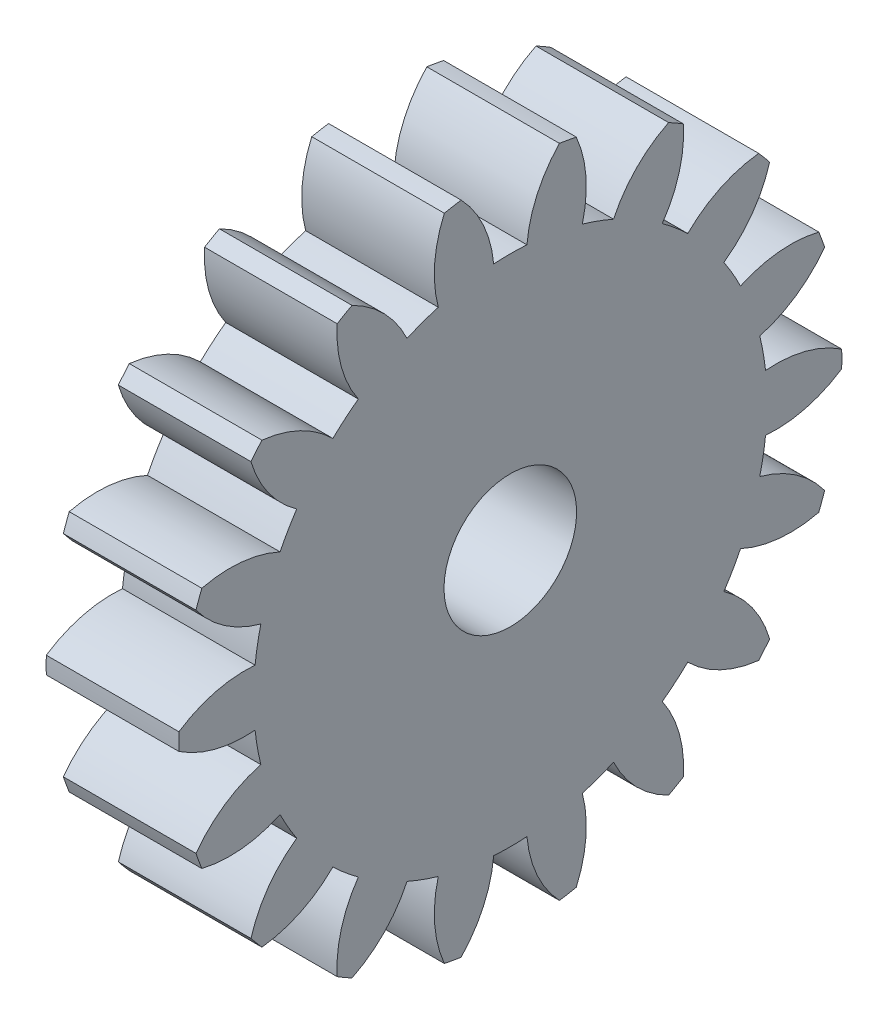
SolidWorks part; units mm, degrees
ref_plane "Plane1" through (0, 0, 0) normal (0, 0, 1) x (1, 0, 0)
ref_plane "Plane2" through (0, 0, 0) normal (0, 1, 0) x (1, 0, 0)
ref_plane "Plane3" through (0, 0, 0) normal (1, 0, 0) x (0, 0, -1)
sketch "HoldingSke" plane through (0, 0, 0) normal (0, 1, 0) x (1, 0, 0)
  line L0 (0, 0) -> (3.8042, -1.2361)
  line L1 (-15, 0) -> (100, 0) construction
  line L2 (0, 0) -> (-2.1039, 2.3779)
  line L3 (0, 0) -> (-11.863, 4.5341)
  line L4 (0, 0) -> (8.2133, 2.6687)
  line L5 (0, 0) -> (-46.8476, -17.4728)
  line L6 (0, 0) -> (-0.829, -0.5593)
  line L7 (-2.1039, 2.3779) -> (8.6586, 51.2059)
  line L8 (-76.2, 54.61) -> (-76.1, 54.61)
  line L9 (-71.009, 38.7566) -> (-53.1078, 45.2721)
  line L10 (-76.2, 71.12) -> (104.1128, 71.12)
  line L11 (0, 0) -> (-1, 0)
  line L12 (-76.2, 101.6) -> (-76.192, 101.6)
  line L13 (24.9733, 27.94) -> (52.9518, 28.4284)
  line L14 (24.9733, 27.94) -> (24.9743, 27.94)
  line L15 (24.9733, 27.94) -> (100.4006, 29.5858)
  line L16 (-63.627, -0.25) -> (-12.827, -0.25)
  circle A0 centre (0, 0) radius 0.625
  circle A1 centre (0, 0) radius 1.9365
  circle A2 centre (0, 0) radius 37.5
  circle A3 centre (0, 0) radius 0.625
  dimension "MHD" = 3.873
  dimension "Hub_dia" = 75
  dimension "Bore" = 1.25
  dimension "MBD" = 1.25
  dimension "Num_teeth" = 18
  dimension "Pitch" = 4
  dimension "Overall_len" = 50
  dimension "Show_teeth" = 18
  dimension "Thickness" = 1
  dimension "OAL" = 50.0001
  dimension "T_dim" = 0.1
  dimension "Ap" = 20
  dimension "H" = 19.05
  dimension "Pitch_radius" = 180.3128
  dimension "Width" = 1
  dimension "Backlash" = 0.008
  dimension "Addendum_fac" = 1
  dimension "Dedendum_fac" = 1.25
  dimension "Clearance_fac" = 0.25
  dimension "Dedendum_add" = 0.001
  dimension "Module" = 0.25
sketch "BasProSke" plane through (0, 0, 0) normal (0, 1, 0) x (1, 0, 0)
  line L0 (-10, 0) -> (60, 0) construction
  line L1 (0, 0) -> (0, 2.5)
  line L2 (0, 0) -> (1, 0)
  line L3 (1, 0) -> (1, 2.5)
  line L4 (1, 2.5) -> (0, 2.5)
  dimension "Thickness" = 1
  dimension "Diameter" = 5
revolve "Base-Revolve" add sketch "BasProSke" angle 360 about L0
sketch "TooCutSke" plane through (0, 0, 0) normal (1, 0, 0) x (0, 0, -1)
  line L1 (0, 0) -> (0, 107) construction
  line L2 (0, 0) -> (-0.2101, 2.2402) construction
  line L3 (0, 0) -> (-0.7789, 4.4171) construction
  line L4 (-0.2101, 2.2402) -> (-0.3894, 2.2085) construction
  arc A0 (0.1253, 1.9324) -> (-0.1253, 1.9324) centre (0, 0) ccw
  arc A1 (0.3925, 2.4947) -> (-0.3925, 2.4947) centre (0, 0) ccw
  circle A2 centre (0, 0) radius 2.25 construction
  circle A3 centre (0, 0) radius 2.1143 construction
  arc A4 (-0.1253, 1.9324) -> (-0.3925, 2.4947) centre (-1.0216, 1.8511) ccw
  arc A5 (0.3925, 2.4947) -> (0.1253, 1.9324) centre (1.0216, 1.8511) ccw
  dimension "Root_dia" = 3.873
  dimension "Overcut_dia" = 5.0508
  dimension "Pitch_dia" = 4.5
  dimension "Base_dia" = 4.2286
  dimension "Flank_rad" = 0.9
  dimension "Half_ang" = 10
  dimension "Half_CT" = 0.1821
extrude "ToothCut" cut sketch "TooCutSke" along normal through all
fillet "Breaks" [suppressed] radius 0.005
fillet "RootFillets" [suppressed] radius 0.0635
pattern_circular "TeethCuts" count 18 every 20 about axis through (-10, 0, 0) along (1, 0, 0) of "ToothCut", "RootFillets", "Breaks"
sketch "HubNeaOneSke" plane through (0, 0, 0) normal (-1, 0, 0) x (0, 0, 1)
  circle A0 centre (0, 0) radius 1.9365
  dimension "Diameter" = 3.873
extrude "HubNearOne" [suppressed] add sketch "HubNeaOneSke" along normal blind 49.0001
sketch "HubNeaBotSke" plane through (0, 0, 0) normal (-1, 0, 0) x (0, 0, 1)
  circle A0 centre (0, 0) radius 1.9365
  dimension "Diameter" = 3.873
extrude "HubNearBoth" [suppressed] add sketch "HubNeaBotSke" along normal blind 24.5
ref_plane "FarPln" through (1, 0, 0) normal (1, 0, 0) x (0, 0, -1)
sketch "HubFarSke" plane through (1, 0, 0) normal (1, 0, 0) x (0, 0, -1)
  circle A0 centre (0, 0) radius 1.9365
  dimension "Diameter" = 3.873
extrude "HubFar" [suppressed] add sketch "HubFarSke" along normal blind 24.5
sketch "BorSke" plane through (0, 0, 0) normal (1, 0, 0) x (0, 0, -1)
  circle A0 centre (0, 0) radius 0.5
  dimension "Diameter" = 1
extrude "Bore" cut sketch "BorSke" along normal mid plane 100.0001
sketch "KeySke" plane through (0, 0, 0) normal (1, 0, 0) x (0, 0, -1)
  line L0 (-0.05, 0) -> (-0.05, 0.725)
  line L1 (-0.05, 0.725) -> (0.05, 0.725)
  line L2 (0.05, 0.725) -> (0.05, 0)
  line L3 (0, 0) -> (0, 34) construction
  line L4 (-0.05, 0) -> (0.05, 0)
  dimension "Offset" = 0.725
extrude "Keyway" [suppressed] cut sketch "KeySke" along normal mid plane 100.0001
pattern_circular "Keyway2" [suppressed] count 2 every 90 about axis through (-10, 0, 0) along (1, 0, 0)
equation "' \"Module@HoldingSke\" = 6.35"
equation "' \"Num_teeth@HoldingSke\" = 12"
equation "' \"Ap@HoldingSke\" =  20"
equation "' \"Ap@HoldingSke\" = 20"
equation "' \"Width@HoldingSke\" = 0.5 * 25.4"
equation "' \"Hub_dia@HoldingSke\"= 1 * 25.4"
equation "' \"Hub_dia@HoldingSke\" = 1 * 25.4"
equation "' \"Overall_len@HoldingSke\" = 1.0 * 25.4"
equation "' \"Bore@HoldingSke\" = 0.75 * 25.4"
equation "' \"T_dim@HoldingSke\" = 0.1 * 25.4"
equation "' \"Width@KeySke\" = 0.25 * 25.4"
equation "' \"Show_teeth@HoldingSke\" = 13"
equation "' \"Backlash@HoldingSke\" = 0.009 * 25.4"
equation "' \"Addendum_fac@HoldingSke\" = 1.0"
equation "' \"Dedendum_fac@HoldingSke\" = 1.25"
equation "' \"Dedendum_add@HoldingSke\" = 0.00005 * 25.4"
equation "' \"Clearance_fac@HoldingSke\" = 0.25"
equation "\"Pitch@HoldingSke\" = 1 / \"Module@HoldingSke\""
equation "\"Overcut_dia@TooCutSke\" = (\"Num_teeth@HoldingSke\" + 2 * \"Addendum_fac@HoldingSke\") / \"Pitch@HoldingSke\" + 0.002 * 25.4"
equation "\"Pitch_dia@TooCutSke\" = \"Num_teeth@HoldingSke\" / \"Pitch@HoldingSke\""
equation "\"Base_dia@TooCutSke\" = \"Num_teeth@HoldingSke\" / \"Pitch@HoldingSke\" * cos((\"Ap@HoldingSke\"  * 3.14159265 / 180))"
equation "\"Root_dia@TooCutSke\" = (\"Num_teeth@HoldingSke\" + 2) / \"Pitch@HoldingSke\" - 2 * (\"Addendum_fac@HoldingSke\" + \"Dedendum_fac@HoldingSke\") / \"Pitch@HoldingSke\" - \"Dedendum_add@HoldingSke\" * 2"
equation "\"Half_ang@TooCutSke\" = 180 / \"Num_teeth@HoldingSke\""
equation "\"Half_CT@TooCutSke\" = \"Num_teeth@HoldingSke\" / \"Pitch@HoldingSke\" * sin((3.14159265 / 2 / \"Num_teeth@HoldingSke\")) / 2 - 7 * \"Backlash@HoldingSke\" / 4"
equation "\"Flank_rad@TooCutSke\" = \"Num_teeth@HoldingSke\" / \"Pitch@HoldingSke\" / 5"
equation "\"Radius@RootFillets\" = \"Clearance_fac@HoldingSke\" / \"Pitch@HoldingSke\" + \"Dedendum_add@HoldingSke\""
equation "\"Break_rad@Breaks\" = 0.02 / \"Pitch@HoldingSke\""
equation "\"Thickness@HoldingSke\" = \"Width@HoldingSke\""
equation "\"OAL@HoldingSke\" = \"Thickness@HoldingSke\""
equation "\"MHD@HoldingSke\" = (\"Num_teeth@HoldingSke\" + 2) / \"Pitch@HoldingSke\" - 2 * (\"Addendum_fac@HoldingSke\" + \"Dedendum_fac@HoldingSke\")  / \"Pitch@HoldingSke\" - \"Dedendum_add@HoldingSke\" * 2"
equation "\"MBD@HoldingSke\" = (\"Num_teeth@HoldingSke\" + 2) / \"Pitch@HoldingSke\" - 2 * (\"Addendum_fac@HoldingSke\" + \"Dedendum_fac@HoldingSke\")  / \"Pitch@HoldingSke\" - \"Dedendum_add@HoldingSke\" * 2 - 0.002 * 25.4"
equation "\"MHD@HoldingSke\" = ((sgn( \"MHD@HoldingSke\" - \"Hub_dia@HoldingSke\" )-1)*( \"MHD@HoldingSke\" - \"Hub_dia@HoldingSke\" ))/-2+ \"Hub_dia@HoldingSke\""
equation "\"MBD@HoldingSke\" = ((sgn( \"MBD@HoldingSke\" - \"Bore@HoldingSke\" )-1)*( \"MBD@HoldingSke\" - \"Bore@HoldingSke\" ))/-2+ \"Bore@HoldingSke\""
equation "\"OAL@HoldingSke\" = ((sgn( \"OAL@HoldingSke\" - \"Overall_len@HoldingSke\" )+1)*( \"OAL@HoldingSke\" - \"Overall_len@HoldingSke\" ))/2 + \"Overall_len@HoldingSke\" + 0.000002 * 25.4"
equation "\"Num_teeth@TeethCuts\" = int( \"Show_teeth@HoldingSke\" ) + 1"
equation "\"Num_teeth@TeethCuts\" = ((sgn( \"Num_teeth@TeethCuts\" - \"Num_teeth@HoldingSke\" )-1)*( \"Num_teeth@TeethCuts\" - \"Num_teeth@HoldingSke\" ))/-2+ \"Num_teeth@HoldingSke\""
equation "\"Num_teeth@TeethCuts\" = ((sgn( \"Num_teeth@TeethCuts\" - 2.0)+1)*( \"Num_teeth@TeethCuts\" - 2.0))/2 +2.0"
equation "\"Angle@TeethCuts\" = 360.0 / \"Num_teeth@HoldingSke\""
equation "\"Diameter@BasProSke\" = (\"Num_teeth@HoldingSke\" + 2 * \"Addendum_fac@HoldingSke\") / \"Pitch@HoldingSke\""
equation "\"Thickness@BasProSke\"  = \"Thickness@HoldingSke\""
equation "' \"Fillet_rad@BasProSke\" =  \"Thickness@HoldingSke\" * 0.05"
equation "' \"Fillet_rad@BasProSke\" = \"Thickness@HoldingSke\" * 0.05"
equation "\"MHD@HoldingSke\" = ((sgn( \"MHD@HoldingSke\" - \"Root_dia@TooCutSke\" )-1)*( \"MHD@HoldingSke\" - \"Root_dia@TooCutSke\" ))/-2+ \"Root_dia@TooCutSke\""
equation "\"Diameter@HubNeaOneSke\" = \"MHD@HoldingSke\""
equation "\"Length@HubNearOne\" = \"OAL@HoldingSke\" - \"Thickness@BasProSke\""
equation "\"Diameter@HubNeaBotSke\" = \"MHD@HoldingSke\""
equation "\"Length@HubNearBoth\" = ( \"OAL@HoldingSke\" - \"Thickness@BasProSke\" ) / 2.0"
equation "\"Thickness@FarPln\" = \"Thickness@BasProSke\""
equation "\"Diameter@HubFarSke\" = \"MHD@HoldingSke\""
equation "\"Length@HubFar\" = ( \"OAL@HoldingSke\" - \"Thickness@BasProSke\" ) / 2.0"
equation "\"D1@Bore\" = \"OAL@HoldingSke\" * 2.0"
equation "\"D1@Keyway\" = \"OAL@HoldingSke\" * 2.0"
equation "\"Offset@KeySke\" = \"T_dim@HoldingSke\" + \"MBD@HoldingSke\" / 2.0"
